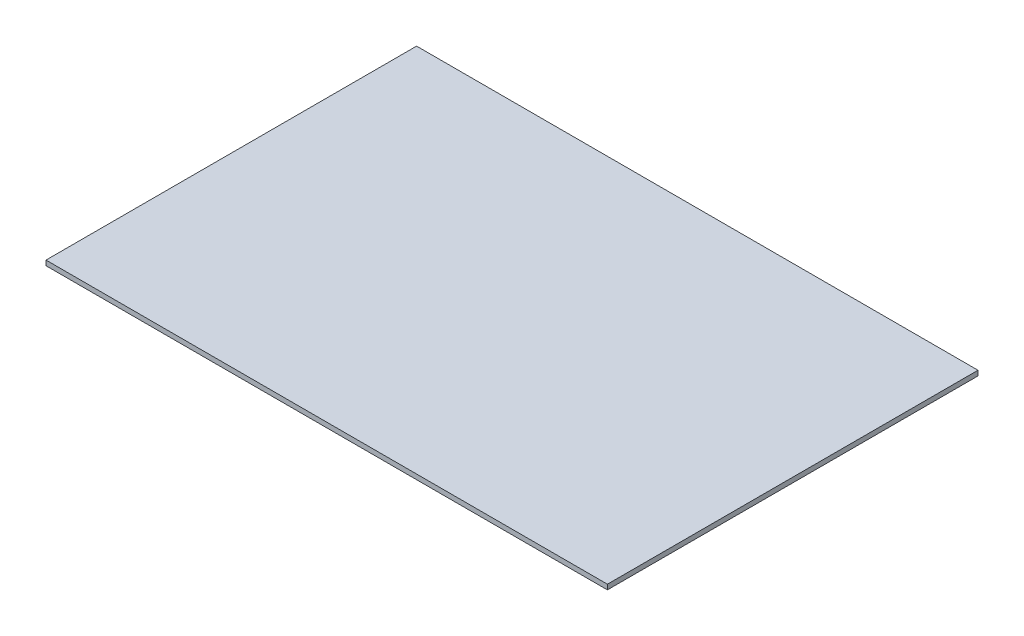
SolidWorks part; units mm, degrees
material "Nylon 6/10"
ref_plane "Front Plane" through (0, 0, 0) normal (0, 0, 1) x (1, 0, 0)
ref_plane "Top Plane" through (0, 0, 0) normal (0, 1, 0) x (1, 0, 0)
ref_plane "Right Plane" through (0, 0, 0) normal (1, 0, 0) x (0, 0, -1)
sketch "Sketch2" plane through (0, 0, 0) normal (0, 1, 0) x (1, 0, 0)
  line L0 (0, 0) -> (22.7237, 0)
  line L1 (22.7237, 0) -> (22.7237, 15)
  line L2 (22.7237, 15) -> (0, 15)
  line L3 (0, 15) -> (0, 0)
extrude "Boss-Extrude1" add sketch "Sketch2" along normal blind 0.2
